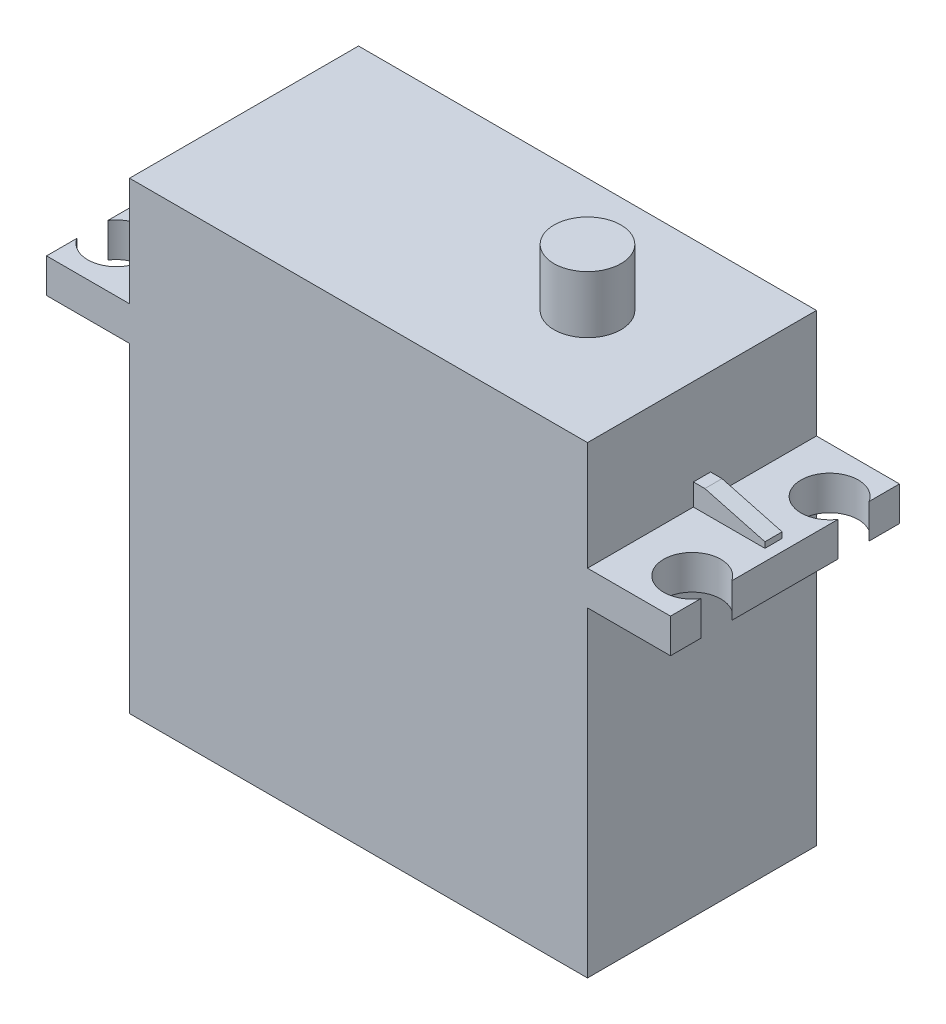
SolidWorks part; units mm, degrees
ref_plane "Front Plane" through (0, 0, 0) normal (0, 0, 1) x (1, 0, 0)
ref_plane "Top Plane" through (0, 0, 0) normal (0, 1, 0) x (1, 0, 0)
ref_plane "Right Plane" through (0, 0, 0) normal (1, 0, 0) x (0, 0, -1)
sketch "Sketch1" plane through (0, 0, 0) normal (0, 1, 0) x (1, 0, 0)
  line L1 (20, 10) -> (-20, 10)
  line L2 (20, 10) -> (20, -10)
  line L3 (20, -10) -> (-20, -10)
  line L4 (-20, 10) -> (-20, -10)
  line L5 (20, 10) -> (-20, -10) construction
  line L6 (20, -10) -> (-20, 10) construction
  point P0 (0, 0)
  dimension "D1" = 40
  dimension "D2" = 20
extrude "Boss-Extrude1" add sketch "Sketch1" against normal blind 28
sketch "Sketch2" plane through (0, 0, 0) normal (0, 1, 0) x (1, 0, 0)
  line L0 (-20, -10) -> (20, -10) construction
  line L1 (27.25, 10) -> (-27.25, 10)
  line L2 (27.25, 10) -> (27.25, -10)
  line L3 (27.25, -10) -> (-27.25, -10)
  line L4 (-27.25, 10) -> (-27.25, -10)
  line L5 (27.25, 10) -> (-27.25, -10) construction
  line L6 (27.25, -10) -> (-27.25, 10) construction
  point P0 (0, 0)
  dimension "D1" = 54.5
extrude "Boss-Extrude2" add sketch "Sketch2" along normal blind 3
sketch "Sketch3" plane through (0, 3, 0) normal (0, 1, 0) x (1, 0, 0)
  line L4 (-20, 10) -> (-20, -10)
  line L5 (20, 10) -> (-20, 10)
  line L6 (20, -10) -> (20, 10)
  line L7 (-20, -10) -> (20, -10)
  line L8 (-20, 10) -> (-20, -10)
  line L9 (20, 10) -> (-20, 10)
  line L10 (20, -10) -> (20, 10)
  line L11 (-20, -10) -> (20, -10)
  dimension "D1" = 0
extrude "Boss-Extrude3" add sketch "Sketch3" along normal blind 9.5
sketch "Sketch4" plane through (0, 12.5, 0) normal (0, 1, 0) x (1, 0, 0)
  line L0 (20, -10) -> (20, 10) construction
  circle A0 centre (10, 0) radius 2.925
  dimension "D1" = 5.85
  dimension "D2" = 10
extrude "Boss-Extrude4" add sketch "Sketch4" along normal blind 5
sketch "Sketch5" plane through (0, 3, 0) normal (0, 1, 0) x (1, 0, 0)
  line L0 (20, -10) -> (27.25, -10) construction
  line L1 (27.25, -10) -> (27.25, 10) construction
  line L2 (27.25, -10) -> (27.25, 10) construction
  line L3 (27.25, 10) -> (20, 10) construction
  line L4 (-27.25, 10) -> (-27.25, -10) construction
  line L5 (-27.25, -10) -> (-20, -10) construction
  line L6 (-20, 10) -> (-27.25, 10) construction
  circle A0 centre (25.15, -6) radius 2.5
  circle A1 centre (25.15, 6) radius 2.5
  circle A2 centre (-25.15, -6) radius 2.5
  circle A3 centre (-25.15, 6) radius 2.5
  dimension "D1" = 4
  dimension "D2" = 5
  dimension "D4" = 2.1
  dimension "D6" = 5
  dimension "D7" = 5
  dimension "D8" = 5
  dimension "D3" = 2.1
  dimension "D5" = 4
  dimension "D9" = 2.1
  dimension "D10" = 2.1
  dimension "D11" = 4
  dimension "D12" = 4
extrude "Cut-Extrude1" cut sketch "Sketch5" against normal up to surface (3 mm away) up to face at (23.625, 0, 0)
sketch "Sketch6" plane through (0, 0, -10) normal (0, 0, -1) x (-1, 0, 0)
  line L0 (-20, 3) -> (-20, 4.9)
  line L1 (-20, 12.5) -> (-20, 3) construction
  line L4 (-27.25, 3) -> (-20, 3) construction
  line L5 (-26.25, 3) -> (-20, 3)
  line L6 (-20, 4.9) -> (-21, 4.9)
  line L8 (-26.25, 3) -> (-26.25, 3.5)
  line L9 (-26.25, 3.5) -> (-21, 4.9)
  line L10 (-27.25, 0) -> (-27.25, 3) construction
  dimension "D1" = 1.9
  dimension "D2" = 1
  dimension "D3" = 1
  dimension "D4" = 0.5
extrude "Boss-Extrude5" add sketch "Sketch6" along normal blind 0.75 and the other way blind 0.75 from offset 10 offset against normal yes
mirror "Mirror1" about plane through (0, 0, 0) normal (1, 0, 0) of "Boss-Extrude5"
